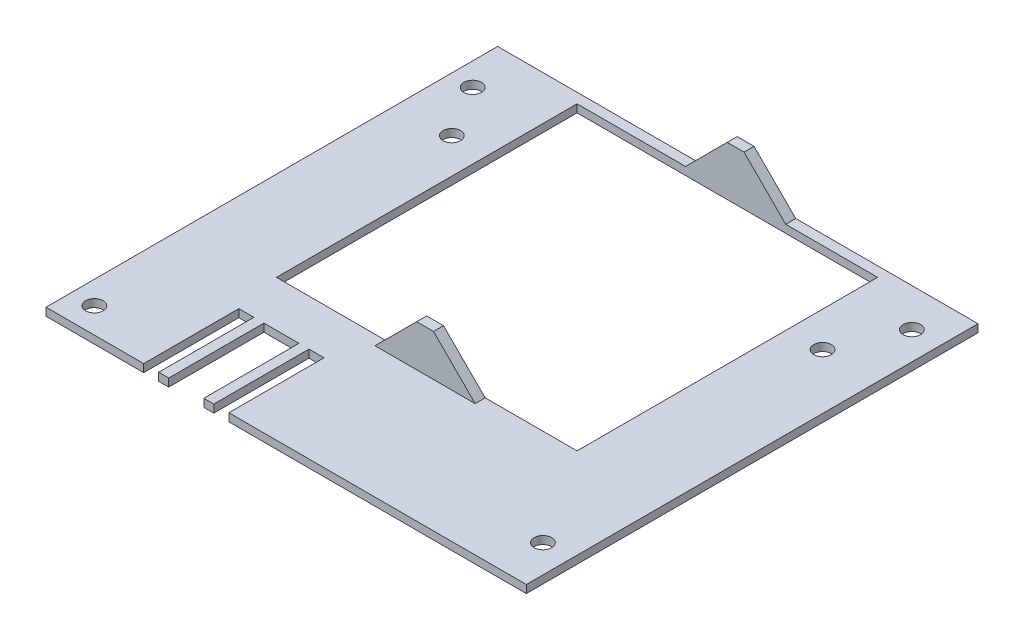
SolidWorks part; units mm, degrees
material "ABS"
ref_plane "Front Plane" through (0, 0, 0) normal (0, 0, 1) x (1, 0, 0)
ref_plane "Top Plane" through (0, 0, 0) normal (0, 1, 0) x (1, 0, 0)
ref_plane "Right Plane" through (0, 0, 0) normal (1, 0, 0) x (0, 0, -1)
sketch "Sketch1" plane through (0, 0, 0) normal (0, 1, 0) x (1, 0, 0)
  line L1 (-32.2441, 108.719) -> (64.6459, 108.719)
  line L2 (-32.2441, 108.719) -> (-32.2441, 18.549)
  line L3 (-32.2441, 18.549) -> (64.6459, 18.549)
  line L4 (64.6459, 108.719) -> (64.6459, 18.549)
  dimension "D1" = 96.89
  dimension "D2" = 90.17
extrude "PCB" add sketch "Sketch1" along normal blind 1.57
sketch "Sketch2" plane through (0, 1.57, 0) normal (0, 1, 0) x (1, 0, 0)
  line L1 (-32.2441, 18.549) -> (64.6459, 18.549) construction
  line L3 (-32.2441, 108.719) -> (-32.2441, 18.549) construction
  circle A0 centre (58.5659, 27.439) radius 1.75
  circle A1 centre (-27.1641, 23.629) radius 1.75
  circle A2 centre (-27.1641, 99.139) radius 1.75
  circle A3 centre (58.5659, 101.099) radius 1.75
  dimension "D3" = 3.5
  dimension "D6" = 3.5
  dimension "D11" = 3.5
  dimension "D12" = 3.5
  dimension "D2" = 8.89
  dimension "D4" = 5.08
  dimension "D5" = 5.08
  dimension "D7" = 5.08
  dimension "D8" = 90.81
  dimension "D9" = 82.55
  dimension "D10" = 80.59
  dimension "D13" = 90.81
extrude "M3 Mounting Holes" cut sketch "Sketch2" against normal blind 1.57
sketch "Sketch3" plane through (0, 1.57, 0) normal (0, 1, 0) x (1, 0, 0)
  line L0 (64.6459, 108.719) -> (-32.2441, 108.719) construction
  line L1 (12.7559, 108.719) -> (22.7559, 108.719)
  line L2 (12.7559, 108.719) -> (12.7559, 106.719)
  line L3 (12.7559, 106.719) -> (22.7559, 106.719)
  line L4 (22.7559, 108.719) -> (22.7559, 106.719)
  line L5 (-32.2441, 108.719) -> (-32.2441, 18.549) construction
  line L7 (12.7559, 46.719) -> (22.7559, 46.719)
  line L8 (12.7559, 46.719) -> (12.7559, 44.719)
  line L9 (12.7559, 44.719) -> (22.7559, 44.719)
  line L10 (22.7559, 46.719) -> (22.7559, 44.719)
  dimension "D1" = 2
  dimension "D2" = 10
  dimension "D3" = 0
  dimension "D4" = 45
  dimension "D5" = 60
  dimension "D6" = 2
  dimension "D7" = 45
extrude "Boss-Extrude1" [suppressed] add sketch "Sketch3" along normal blind 10
sketch "Sketch4" plane through (0, 1.57, 0) normal (0, 1, 0) x (1, 0, 0)
  line L0 (64.6459, 108.719) -> (-32.2441, 108.719) construction
  line L1 (64.6459, 108.719) -> (-32.2441, 108.719) construction
  line L2 (-32.2441, 108.719) -> (-32.2441, 18.549) construction
  circle A0 centre (-20.8941, 88.719) radius 1.75
  circle A1 centre (53.1059, 88.719) radius 1.75
  dimension "D1" = 3.5
  dimension "D2" = 3.5
  dimension "D3" = 20
  dimension "D4" = 20
  dimension "D5" = 74
  dimension "D6" = 11.35
extrude "Cut-Extrude1" cut sketch "Sketch4" against normal blind 23
ref_plane "Plane1" through (0, 0, -46.719) normal (0, 0, 1) x (1, 0, 0)
sketch "Sketch7" plane through (0, 0, -46.719) normal (0, 0, 1) x (1, 0, 0)
  line L0 (27.7559, 1.57) -> (19.4384, 9.8875)
  line L1 (19.4384, 9.8875) -> (16.0735, 9.8875)
  line L2 (16.0735, 9.8875) -> (7.7559, 1.57)
  line L3 (7.7559, 1.57) -> (27.7559, 1.57)
  line L4 (-32.2441, 1.57) -> (64.6459, 1.57) construction
  dimension "D1" = 45
  dimension "D2" = 45
  dimension "D3" = 0
  dimension "D4" = 3.3649
  dimension "D5" = 20
  dimension "D6" = 5
ref_plane "Plane2" through (0, 0, -108.719) normal (0, 0, 1) x (1, 0, 0)
sketch "Sketch8" plane through (0, 0, -108.719) normal (0, 0, 1) x (1, 0, 0)
  line L0 (27.7559, 1.57) -> (19.4384, 9.8875) construction
  line L1 (19.4384, 9.8875) -> (16.0735, 9.8875) construction
  line L2 (16.0735, 9.8875) -> (7.7559, 1.57) construction
  line L3 (7.7559, 1.57) -> (27.7559, 1.57) construction
  line L4 (27.7559, 1.57) -> (19.4384, 9.8875)
  line L5 (19.4384, 9.8875) -> (16.0735, 9.8875)
  line L6 (16.0735, 9.8875) -> (7.7559, 1.57)
  line L7 (7.7559, 1.57) -> (27.7559, 1.57)
extrude "Boss-Extrude2" add sketch "Sketch7" along normal blind 2
extrude "Boss-Extrude3" add sketch "Sketch8" along normal blind 2
sketch "Sketch9" plane through (0, 1.57, 0) normal (0, 1, 0) x (1, 0, 0)
  line L0 (-32.2441, 18.549) -> (64.6459, 18.549) construction
  line L1 (-9.2441, 18.549) -> (-12.2441, 18.549)
  line L2 (-9.2441, 18.549) -> (-9.2441, 37.549)
  line L3 (-9.2441, 37.549) -> (-12.2441, 37.549)
  line L4 (-12.2441, 18.549) -> (-12.2441, 37.549)
  line L5 (-32.2441, 108.719) -> (-32.2441, 18.549) construction
  line L6 (-7.2441, 18.549) -> (-0.2441, 18.549)
  line L7 (-7.2441, 18.549) -> (-7.2441, 37.549)
  line L8 (-7.2441, 37.549) -> (-0.2441, 37.549)
  line L9 (-0.2441, 18.549) -> (-0.2441, 37.549)
  line L11 (1.7559, 18.549) -> (4.7559, 18.549)
  line L12 (1.7559, 18.549) -> (1.7559, 37.549)
  line L13 (1.7559, 37.549) -> (4.7559, 37.549)
  line L14 (4.7559, 18.549) -> (4.7559, 37.549)
  dimension "D1" = 19
  dimension "D2" = 19
  dimension "D3" = 2
  dimension "D4" = 3
  dimension "D5" = 7
  dimension "D6" = 20
  dimension "D7" = 3
  dimension "D8" = 19
  dimension "D9" = 2
extrude "Cut-Extrude2" cut sketch "Sketch9" against normal through all
sketch "Sketch10" plane through (0, 1.57, 0) normal (0, 1, 0) x (1, 0, 0)
  line L0 (7.7559, 108.719) -> (-32.2441, 108.719) construction
  line L1 (-32.2441, 18.549) -> (-31.7441, 18.549)
  line L2 (-32.2441, 18.549) -> (-32.2441, 108.719)
  line L3 (-32.2441, 108.719) -> (-31.7441, 108.719)
  line L4 (-31.7441, 18.549) -> (-31.7441, 108.719)
  line L5 (64.6459, 108.719) -> (27.7559, 108.719) construction
  line L6 (64.6459, 18.549) -> (64.1459, 18.549)
  line L7 (64.6459, 18.549) -> (64.6459, 108.719)
  line L8 (64.6459, 108.719) -> (64.1459, 108.719)
  line L9 (64.1459, 18.549) -> (64.1459, 108.719)
  dimension "D1" = 0.5
  dimension "D2" = 0.5
extrude "Cut-Extrude3" cut sketch "Sketch10" against normal blind 10
sketch "Sketch11" plane through (0, 1.57, 0) normal (0, 1, 0) x (1, 0, 0)
  line L0 (7.7559, 106.719) -> (27.7559, 106.719) construction
  line L1 (-13.8941, 106.719) -> (46.1059, 106.719)
  line L2 (-13.8941, 106.719) -> (-13.8941, 46.719)
  line L3 (-13.8941, 46.719) -> (46.1059, 46.719)
  line L4 (46.1059, 106.719) -> (46.1059, 46.719)
  dimension "D1" = 60
  dimension "D2" = 60
  dimension "D3" = 0
  dimension "D4" = 7
extrude "Cut-Extrude4" cut sketch "Sketch11" against normal blind 10
